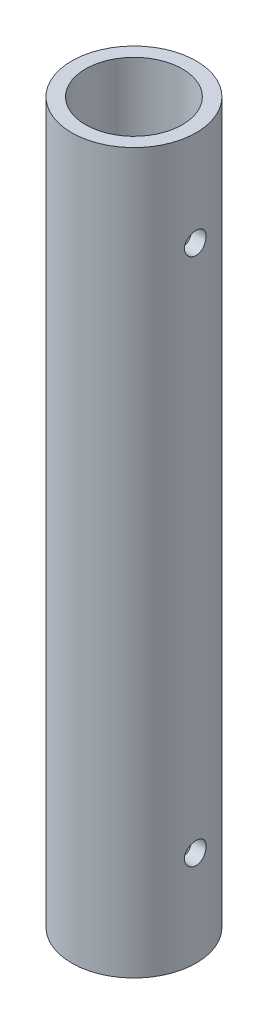
SolidWorks part; units mm, degrees
ref_plane "Front Plane" through (0, 0, 0) normal (0, 0, 1) x (1, 0, 0)
ref_plane "Top Plane" through (0, 0, 0) normal (0, 1, 0) x (1, 0, 0)
ref_plane "Right Plane" through (0, 0, 0) normal (1, 0, 0) x (0, 0, -1)
sketch "Sketch1" plane through (0, 0, 0) normal (0, 1, 0) x (1, 0, 0)
  circle A0 centre (0, 0) radius 14.2875
  circle A1 centre (0, 0) radius 11.1125
  dimension "D1" = 28.575
  dimension "D2" = 3.175
extrude "Boss-Extrude1" add sketch "Sketch1" along normal mid plane 165.1
sketch "Sketch2" plane through (0, 0, 0) normal (1, 0, 0) x (0, 0, -1)
  line L0 (14.2875, 82.55) -> (-14.2875, 82.55) construction
  circle A0 centre (0, 60.6425) radius 2.4892
  point P2 (0, 0)
  dimension "D1" = 4.9784
  dimension "D2" = 21.9075
extrude "Cut-Extrude1" cut sketch "Sketch2" against normal through all both and the other way through all
mirror "Mirror1" about plane through (0, 0, 0) normal (0, 1, 0) of "Cut-Extrude1"
